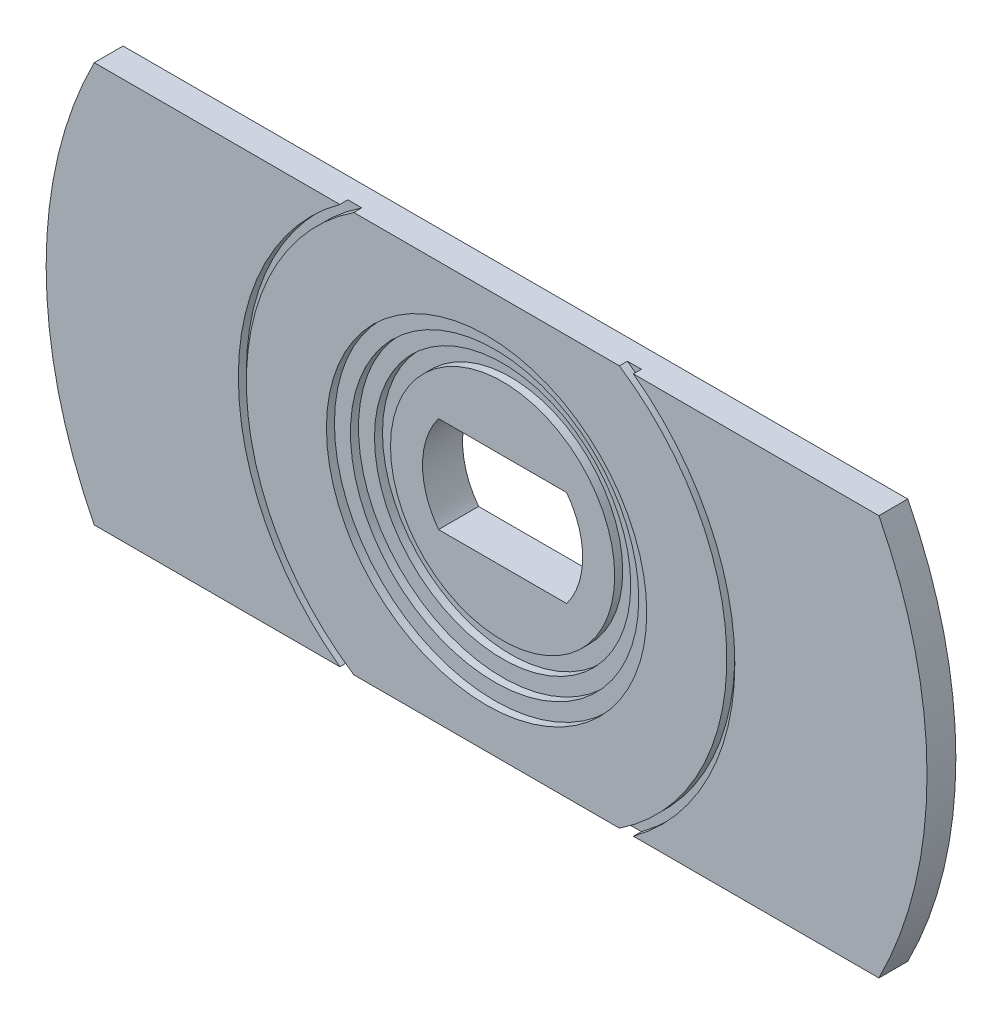
SolidWorks part; units mm, degrees
material "PA Тип 6"
ref_plane "Спереди" through (0, 0, 0) normal (0, 0, 1) x (1, 0, 0)
ref_plane "Сверху" through (0, 0, 0) normal (0, 1, 0) x (1, 0, 0)
ref_plane "Справа" through (0, 0, 0) normal (1, 0, 0) x (0, 0, -1)
sketch "Эскиз1" plane through (0, 0, 0) normal (1, 0, 0) x (0, 0, -1)
  line L0 (0, 29.533) -> (0, -1.8956) construction
  line L1 (-1.4835, 0) -> (10.8242, 0) construction
  line L2 (1.5, 7) -> (1.5, 8)
  line L3 (0, 27.5) -> (1.8, 27.5)
  line L4 (0, 27.5) -> (0, 15.5)
  line L5 (1.5, 7) -> (1.8, 7)
  line L6 (1.8, 27.5) -> (1.8, 7)
  line L7 (1.5, 8) -> (1, 8)
  line L8 (1, 8) -> (1, 9)
  line L9 (1, 9) -> (0.5, 9)
  line L10 (0.5, 9) -> (0.5, 10)
  line L11 (0.5, 10) -> (0, 10)
  line L12 (0, 15) -> (0.5, 15)
  line L13 (0.5, 15) -> (0.5, 15.5)
  line L14 (0.5, 15.5) -> (0, 15.5)
  line L15 (0, 15) -> (0, 10)
  dimension "D1" = 27.5
  dimension "D2" = 7
  dimension "D3" = 1.8
  dimension "D4" = 1
  dimension "D5" = 1
  dimension "D6" = 1
  dimension "D7" = 0.3
  dimension "D8" = 0.5
  dimension "D9" = 0.5
  dimension "D10" = 15
  dimension "D11" = 0.5
  dimension "D12" = 0.5
revolve "Повернуть1" add sketch "Эскиз1" angle 360 about L1
sketch "Эскиз2" plane through (0, 0, 0) normal (0, 0, 1) x (1, 0, 0)
  line L0 (-29.2418, 0) -> (30.9384, 0) construction
  line L1 (-24.4949, 12.5) -> (24.4949, 12.5)
  line L2 (-24.4949, -12.5) -> (24.4949, -12.5)
  circle A1 centre (0, 0) radius 27.5 construction
  circle A2 centre (0, 0) radius 27.5
  arc A3 (-24.4949, -12.5) -> (24.4949, -12.5) centre (0, 0) ccw
  arc A4 (24.4949, 12.5) -> (-24.4949, 12.5) centre (0, 0) ccw
  point P6 (24.4949, 12.5)
  dimension "D2" = 12.5
  dimension "D1" = 0
extrude "Вырез-Вытянуть1" cut sketch "Эскиз2" against normal up to surface (1.8 mm away) up to face at (27.5, 0, -1.8)
sketch "Эскиз3" plane through (0, 0, -1.5) normal (0, 0, 1) x (1, 0, 0)
  line L0 (-29.421, 0) -> (31.1947, 0) construction
  line L1 (4, 3) -> (-4, 3)
  line L2 (4, -3) -> (-4, -3)
  circle A2 centre (0, 0) radius 5
  arc A3 (-4, 3) -> (-4, -3) centre (0, 0) ccw
  arc A4 (4, -3) -> (4, 3) centre (0, 0) ccw
  circle A5 centre (0, 0) radius 7
  circle A6 centre (0, 0) radius 7
  dimension "D3" = 3
  dimension "D1" = 2
  dimension "D2" = 0
extrude "Бобышка-Вытянуть1" add sketch "Эскиз3" against normal blind 2 and the other way blind 0.5
